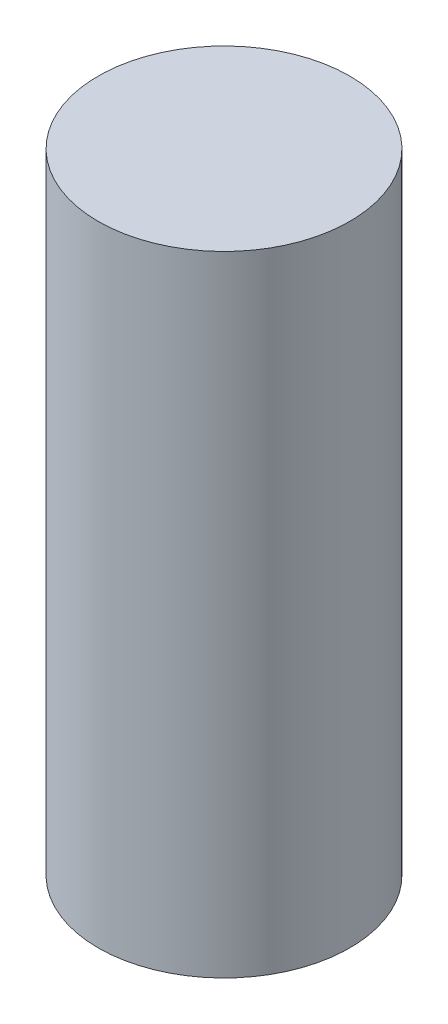
SolidWorks part; units mm, degrees
ref_plane "Front Plane" through (0, 0, 0) normal (0, 0, 1) x (1, 0, 0)
ref_plane "Top Plane" through (0, 0, 0) normal (0, 1, 0) x (1, 0, 0)
ref_plane "Right Plane" through (0, 0, 0) normal (1, 0, 0) x (0, 0, -1)
sketch "Sketch1" plane through (0, 0, 0) normal (0, 1, 0) x (1, 0, 0)
  circle A0 centre (0, 0) radius 40
  dimension "D1" = 80
extrude "Boss-Extrude1" add sketch "Sketch1" along normal blind 200
